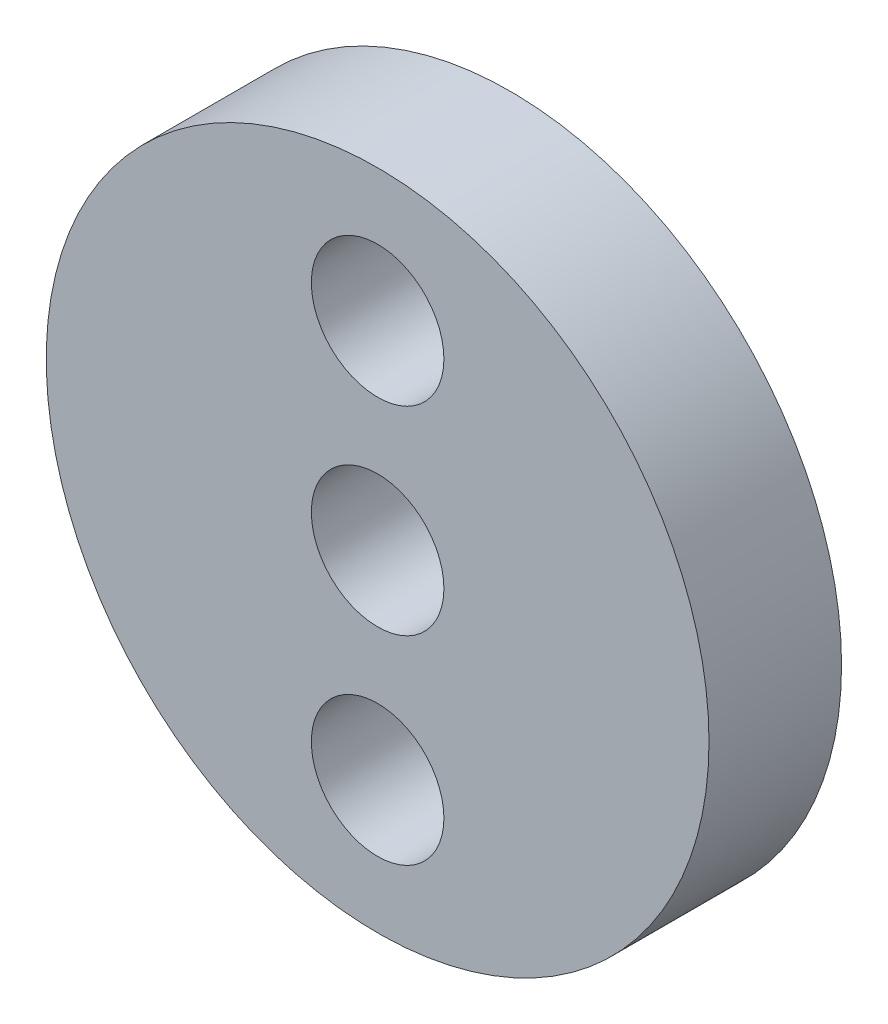
SolidWorks part; units mm, degrees
ref_plane "Plano frontal" through (0, 0, 0) normal (0, 0, 1) x (1, 0, 0)
ref_plane "Plano superior" through (0, 0, 0) normal (0, 1, 0) x (1, 0, 0)
ref_plane "Plano direito" through (0, 0, 0) normal (1, 0, 0) x (0, 0, -1)
sketch "Esboço1" plane through (0, 0, 0) normal (0, 0, 1) x (1, 0, 0)
  circle A0 centre (0, 0) radius 15
  circle A1 centre (0, 0) radius 3
  circle A2 centre (0, 9) radius 3
  circle A3 centre (0, -9) radius 3
  point P8 (0, -9)
  dimension "D1" = 6
  dimension "D2" = 30
  dimension "D3" = 6
  dimension "D4" = 6
  dimension "D5" = 9
  dimension "D6" = 9
extrude "Ressalto-extrusão1" add sketch "Esboço1" along normal blind 6
